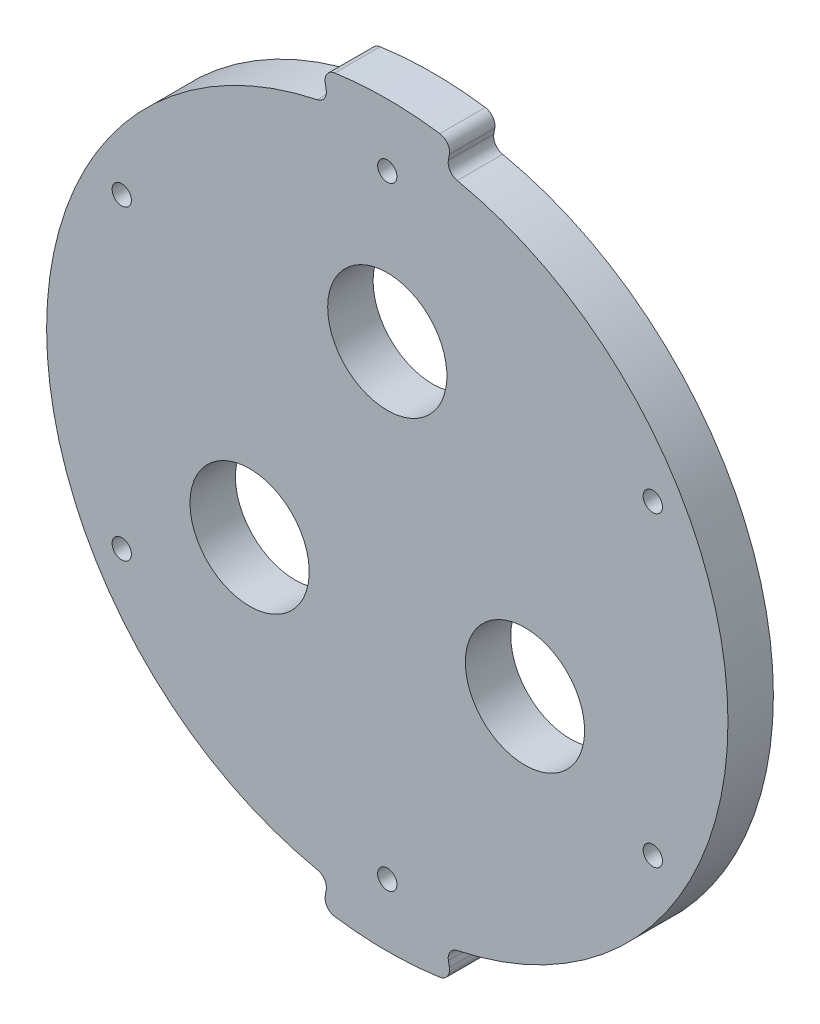
SolidWorks part; units mm, degrees
material "ｱｸﾘﾙ (中-上級の耐衝撃性)"
ref_plane "正面" through (0, 0, 0) normal (0, 0, 1) x (1, 0, 0)
ref_plane "平面" through (0, 0, 0) normal (0, 1, 0) x (1, 0, 0)
ref_plane "右側面" through (0, 0, 0) normal (1, 0, 0) x (0, 0, -1)
sketch "ｽｹｯﾁ1" plane through (0, 0, 0) normal (0, 0, 1) x (1, 0, 0)
  circle A0 centre (0, 0) radius 60
  dimension "D1" = 120
extrude "ﾎﾞｽ - 押し出し1" add sketch "ｽｹｯﾁ1" along normal blind 8
sketch "ｽｹｯﾁ2" plane through (0, 0, 8) normal (0, 0, 1) x (1, 0, 0)
  line L0 (0, 0) -> (0, 65) construction
  line L1 (10.4189, 59.0885) -> (0, 0) construction
  line L2 (10.4189, 59.0885) -> (11.2871, 64.0125)
  line L3 (-10.4189, 59.0885) -> (-11.2871, 64.0125)
  line L4 (10.4189, -59.0885) -> (11.2871, -64.0125)
  line L5 (-10.4189, -59.0885) -> (-11.2871, -64.0125)
  circle A0 centre (0, 0) radius 60 construction
  circle A1 centre (0, 0) radius 65 construction
  arc A2 (-10.4189, 59.0885) -> (10.4189, 59.0885) centre (0, 0) cw
  arc A3 (-11.2871, 64.0125) -> (11.2871, 64.0125) centre (0, 0) cw
  arc A4 (10.4189, -59.0885) -> (-10.4189, -59.0885) centre (0, 0) cw
  arc A5 (11.2871, -64.0125) -> (-11.2871, -64.0125) centre (0, 0) cw
  point P16 (0, 0)
  dimension "D1" = 120
  dimension "D2" = 130
  dimension "D3" = 10
  dimension "D4" = 2
extrude "ﾎﾞｽ - 押し出し2" add sketch "ｽｹｯﾁ2" against normal up to surface (8 mm away) up to face at (60, 0, 0)
fillet "ﾌｨﾚｯﾄ1" radius 2 8 edges at (-11.2871, -64.0125, 4) (-10.4189, -59.0885, 4) (11.2871, -64.0125, 4) (10.4189, -59.0885, 4) (10.4189, 59.0885, 4) (11.2871, 64.0125, 4) (-11.2871, 64.0125, 4) (-10.4189, 59.0885, 4)
sketch "ｽｹｯﾁ6" plane through (0, 0, 0) normal (0, 0, -1) x (-1, 0, 0)
  line L0 (0, 54) -> (0, 0) construction
  point P0 (0, 54)
  point P13 (46.7654, 27)
  point P14 (46.7654, -27)
  point P15 (0, -54)
  point P16 (-46.7654, -27)
  point P17 (-46.7654, 27)
  dimension "D1" = 54
  dimension "D2" = 6
hole_wizard "M3 すきま穴1" positions "ｽｹｯﾁ6" profile "ｽｹｯﾁ7" hole size "M3" standard "JIS" end condition up to next
sketch "ｽｹｯﾁ7" plane through (0, 54, 0) normal (1, 0, 0) x (0, 1, 0)
  line L0 (0, 0) -> (0, 8)
  line L1 (0, 8) -> (1.7, 8)
  line L2 (1.7, 8) -> (1.7, 0.0288)
  line L3 (1.7, 0.0288) -> (1.725, 0)
  line L5 (1.725, 0) -> (0, 0)
  line L6 (-1.7, 0.0288) -> (-1.725, 0) construction
  line L11 (0, -6.35) -> (0, 107.95) construction
  dimension "通し穴の直径" = 3.4
  dimension "通し穴の深さ" = 8
  dimension "表面の皿穴の直径" = 3.45
  dimension "表面の皿穴の角度" = 82
sketch "ｽｹｯﾁ8" plane through (0, 0, 0) normal (0, 0, -1) x (-1, 0, 0)
  line L0 (0, 65) -> (0, -65) construction
  arc A0 (9.2493, 64.3386) -> (-9.2493, 64.3386) centre (0, 0) ccw construction
  arc A1 (-9.2493, -64.3386) -> (9.2493, -64.3386) centre (0, 0) ccw construction
  circle A2 centre (0, 28) radius 10.5
  circle A3 centre (24.2487, -14) radius 10.5
  circle A4 centre (-24.2487, -14) radius 10.5
  point P18 (0, 0)
  dimension "D1" = 21
  dimension "D2" = 28
  dimension "D3" = 3
extrude "ｶｯﾄ - 押し出し1" cut sketch "ｽｹｯﾁ8" against normal through all
sketch "ｽｹｯﾁ9" [suppressed] plane through (0, 0, 0) normal (0, 0, -1) x (-1, 0, 0)
  line L0 (0, 0) -> (0, 65) construction
  arc A0 (9.2493, 64.3386) -> (-9.2493, 64.3386) centre (0, 0) ccw construction
  circle A1 centre (0, 28) radius 10.5
  circle A2 centre (28, 0) radius 10.5
  circle A3 centre (0, -28) radius 10.5
  circle A4 centre (-28, 0) radius 10.5
  point P17 (0, 0)
  dimension "D1" = 21
  dimension "D2" = 28
  dimension "D3" = 4
extrude "ｶｯﾄ - 押し出し2" [suppressed] cut sketch "ｽｹｯﾁ9" against normal through all
